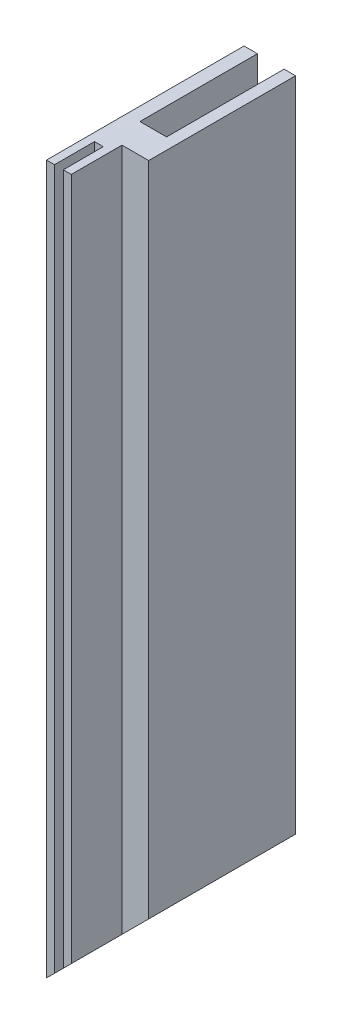
SolidWorks part; units mm, degrees
ref_plane "Front Plane" through (0, 0, 0) normal (0, 0, 1) x (1, 0, 0)
ref_plane "Top Plane" through (0, 0, 0) normal (0, 1, 0) x (1, 0, 0)
ref_plane "Right Plane" through (0, 0, 0) normal (1, 0, 0) x (0, 0, -1)
sketch "Sketch1" plane through (0, 0, 0) normal (0, 1, 0) x (1, 0, 0)
  line L2 (-51.5058, 37) -> (-32.2058, 37)
  line L3 (-32.2058, -18) -> (-42.2058, -18)
  line L4 (-42.2058, -18) -> (-42.2058, -37)
  line L5 (-42.2058, -37) -> (-45.2058, -37)
  line L6 (-45.2058, -37) -> (-45.2058, -22)
  line L7 (-45.2058, -22) -> (-48.5058, -22)
  line L8 (-48.5058, -22) -> (-48.5058, -37)
  line L9 (-48.5058, -37) -> (-51.5058, -37)
  line L10 (-51.5058, -37) -> (-51.5058, 37)
  line L11 (-32.2058, 37) -> (-32.2058, -18)
extrude "Boss-Extrude1" add sketch "Sketch1" along normal blind 265.3
sketch "Sketch2" plane through (0, 265.3, 0) normal (0, 1, 0) x (1, 0, 0)
  line L0 (-46.5058, 37) -> (-36.5058, 37)
  line L1 (-36.5058, 37) -> (-36.5058, -7)
  line L2 (-36.5058, -7) -> (-46.5058, -7)
  line L3 (-46.5058, -7) -> (-46.5058, 37)
  line L4 (-32.2058, 37) -> (-51.5058, 37) construction
  line L5 (-32.2058, -18) -> (-32.2058, 37) construction
  dimension "D1" = 44
  dimension "D2" = 10
  dimension "D3" = 4.3
extrude "Cut-Extrude1" cut sketch "Sketch2" against normal blind 10
ref_plane "Plane1" through (-25.7529, 25.7529, 0) normal (0.7071, -0.7071, 0) x (0, 0, 1)
sketch "Sketch3" plane through (-25.7529, 25.7529, 0) normal (0.7071, -0.7071, 0) x (0, 0, 1)
  line L1 (-132.4991, -59.9961) -> (138.6503, -59.9961)
  line L2 (-132.4991, -59.9961) -> (-132.4991, 99.0438)
  line L3 (-132.4991, 99.0438) -> (138.6503, 99.0438)
  line L4 (138.6503, -59.9961) -> (138.6503, 99.0438)
  line L5 (-132.4991, -59.9961) -> (138.6503, 99.0438) construction
  line L6 (-132.4991, 99.0438) -> (138.6503, -59.9961) construction
  point P0 (3.0756, 19.5239)
extrude "Cut-Extrude2" cut sketch "Sketch3" along normal blind 31
sketch "Sketch4" plane through (-25.7529, 25.7529, 0) normal (0.7071, -0.7071, 0) x (0, 0, -1)
  line L0 (-18, -9.1258) -> (37, -9.1258) construction
  line L1 (25, -22.1258) -> (-3, -22.1258)
  line L2 (25, -22.1258) -> (25, -15.1258)
  line L3 (25, -15.1258) -> (-3, -15.1258)
  line L4 (-3, -22.1258) -> (-3, -15.1258)
  line L5 (37, -9.1258) -> (37, -36.4201) construction
  dimension "D1" = 28
  dimension "D2" = 7
  dimension "D3" = 6
  dimension "D4" = 12
extrude "Cut-Extrude3" cut sketch "Sketch4" against normal blind 8
sketch "Sketch5" plane through (-25.7529, 25.7529, 0) normal (0.7071, -0.7071, 0) x (0, 0, -1)
  line L0 (-3, -15.1258) -> (-3, -22.1258) construction
  line L1 (25.2, -22.3258) -> (-3.2, -22.3258)
  line L2 (25.2, -22.3258) -> (25.2, -14.9258)
  line L3 (25.2, -14.9258) -> (-3.2, -14.9258)
  line L4 (-3.2, -22.3258) -> (-3.2, -14.9258)
  line L5 (25, -22.1258) -> (25, -15.1258) construction
  line L6 (25, -15.1258) -> (-3, -15.1258) construction
  line L7 (-3, -22.1258) -> (25, -22.1258) construction
  dimension "D1" = 0.2
  dimension "D2" = 0.2
  dimension "D3" = 0.2
  dimension "D4" = 0.2
extrude "Cut-Extrude4" cut sketch "Sketch5" against normal up to surface (8 mm away) up to face at (-44.5802, 18.2393, -11)
